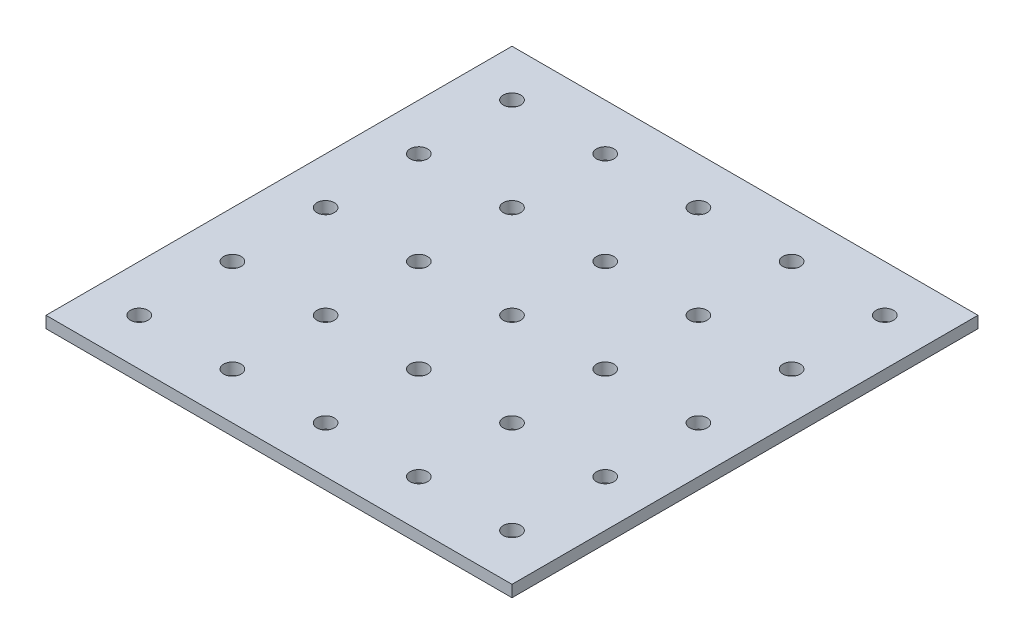
SolidWorks part; units mm, degrees
material "ABS"
ref_plane "Front Plane" through (0, 0, 0) normal (0, 0, 1) x (1, 0, 0)
ref_plane "Top Plane" through (0, 0, 0) normal (0, 1, 0) x (1, 0, 0)
ref_plane "Right Plane" through (0, 0, 0) normal (1, 0, 0) x (0, 0, -1)
sketch "Sketch1" plane through (0, 0, 0) normal (0, 1, 0) x (1, 0, 0)
  line L1 (-63.5, -63.5) -> (63.5, -63.5)
  line L2 (-63.5, -63.5) -> (-63.5, 63.5)
  line L3 (-63.5, 63.5) -> (63.5, 63.5)
  line L4 (63.5, -63.5) -> (63.5, 63.5)
  line L5 (-63.5, -63.5) -> (63.5, 63.5) construction
  line L6 (-63.5, 63.5) -> (63.5, -63.5) construction
  point P0 (0, 0)
  dimension "D1" = 127
  dimension "D2" = 127
extrude "Boss-Extrude1" add sketch "Sketch1" along normal blind 3.175
sketch "Sketch2" plane through (0, 0, 0) normal (0, 1, 0) x (1, 0, 0)
  line L1 (-63.5, -63.5) -> (-50.8, -63.5) construction
  line L2 (-63.5, -63.5) -> (-63.5, -50.8) construction
  line L3 (-63.5, -50.8) -> (-50.8, -50.8) construction
  line L4 (-50.8, -63.5) -> (-50.8, -50.8) construction
  circle A0 centre (-50.8, -50.8) radius 2.3812
  circle A1 centre (-25.4, -50.8) radius 2.3812
  circle A2 centre (0, -50.8) radius 2.3812
  circle A3 centre (25.4, -50.8) radius 2.3812
  circle A4 centre (50.8, -50.8) radius 2.3812
  circle A5 centre (-25.4, -25.4) radius 2.3812
  circle A6 centre (0, -25.4) radius 2.3812
  circle A7 centre (25.4, -25.4) radius 2.3812
  circle A8 centre (50.8, -25.4) radius 2.3812
  circle A9 centre (-25.4, 0) radius 2.3812
  circle A10 centre (0, 0) radius 2.3812
  circle A11 centre (25.4, 0) radius 2.3812
  circle A12 centre (50.8, 0) radius 2.3812
  circle A13 centre (-25.4, 25.4) radius 2.3812
  circle A14 centre (0, 25.4) radius 2.3812
  circle A15 centre (25.4, 25.4) radius 2.3812
  circle A16 centre (50.8, 25.4) radius 2.3812
  circle A17 centre (-25.4, 50.8) radius 2.3812
  circle A18 centre (0, 50.8) radius 2.3812
  circle A19 centre (25.4, 50.8) radius 2.3812
  circle A20 centre (50.8, 50.8) radius 2.3812
  circle A21 centre (-50.8, -25.4) radius 2.3812
  circle A22 centre (-50.8, 0) radius 2.3812
  circle A23 centre (-50.8, 25.4) radius 2.3812
  circle A24 centre (-50.8, 50.8) radius 2.3812
  dimension "D3" = 5
  dimension "D1" = 12.7
  dimension "D2" = 12.7
  dimension "D4" = 5
extrude "Cut-Extrude3" cut sketch "Sketch2" along normal blind 3.175 and the other way through all
